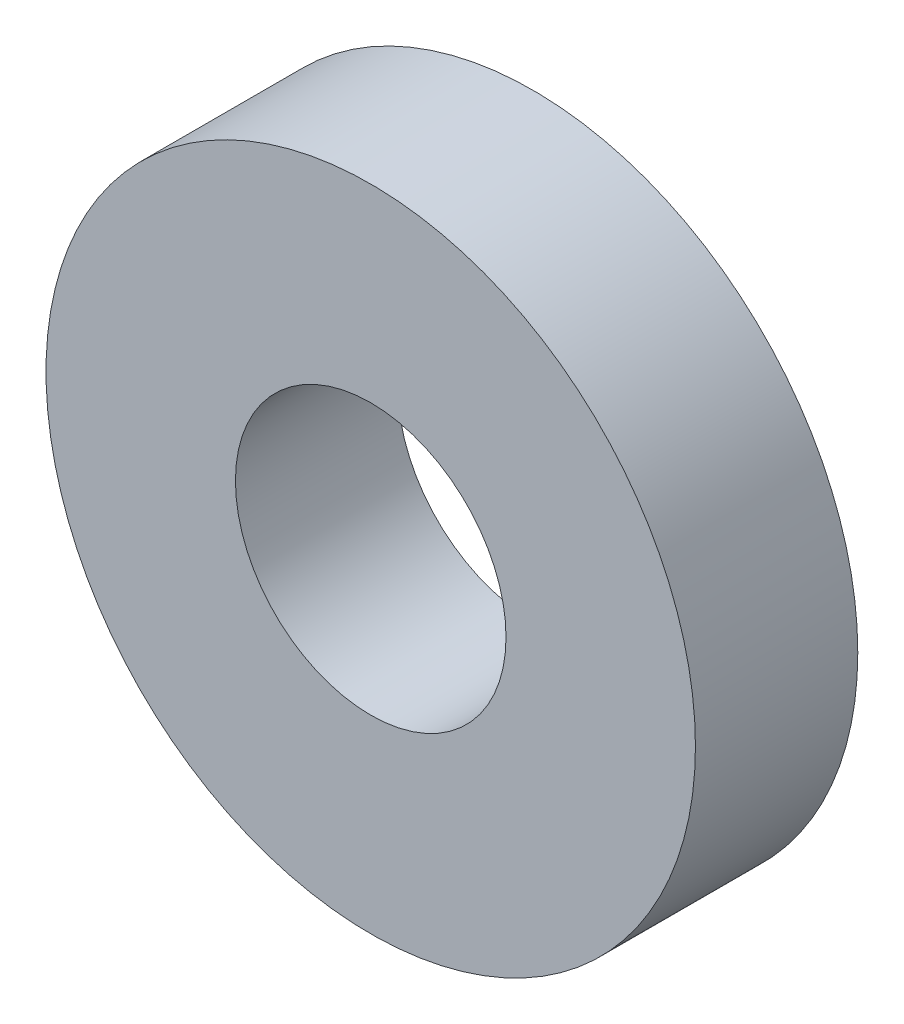
SolidWorks part; units mm, degrees
ref_plane "前视基准面" through (0, 0, 0) normal (0, 0, 1) x (1, 0, 0)
ref_plane "上视基准面" through (0, 0, 0) normal (0, 1, 0) x (1, 0, 0)
ref_plane "右视基准面" through (0, 0, 0) normal (1, 0, 0) x (0, 0, -1)
other "Configuration Table"
sketch "草图8" plane through (0, 0, 0) normal (0, 0, 1) x (1, 0, 0)
  circle A0 centre (0, 0) radius 60
  circle A1 centre (0, 0) radius 25
extrude "凸台-拉伸1" add sketch "草图8" along normal blind 30
